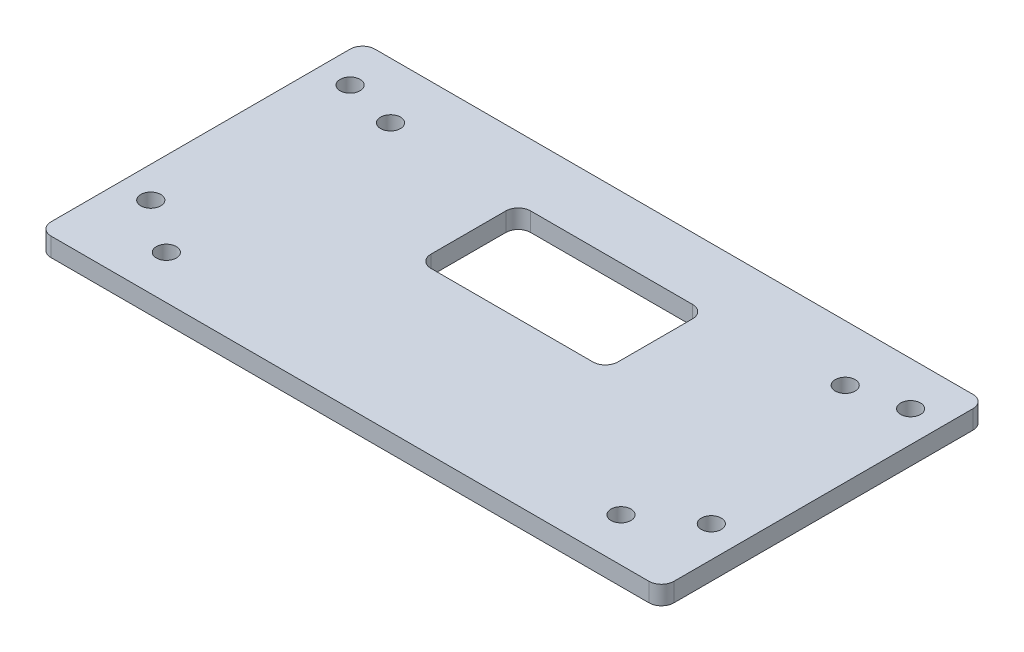
SolidWorks part; units mm, degrees
ref_plane "前视基准面" through (0, 0, 0) normal (0, 0, 1) x (1, 0, 0)
ref_plane "上视基准面" through (0, 0, 0) normal (0, 1, 0) x (1, 0, 0)
ref_plane "右视基准面" through (0, 0, 0) normal (1, 0, 0) x (0, 0, -1)
sketch "草图1" plane through (0, 0, 0) normal (0, 1, 0) x (1, 0, 0)
  line L0 (0, 26) -> (0, -26) construction
  line L1 (-50, -26) -> (50, -26)
  line L2 (-50, -26) -> (-50, 26)
  line L3 (-50, 26) -> (50, 26)
  line L4 (50, -26) -> (50, 26)
  line L5 (-50, -26) -> (50, 26) construction
  line L6 (-50, 26) -> (50, -26) construction
  line L7 (-50, 0) -> (50, 0) construction
  line L9 (-13, 0) -> (13, 0)
  line L10 (-15, 2) -> (-15, 14)
  line L11 (-13, 16) -> (13, 16)
  line L12 (15, 2) -> (15, 14)
  line L13 (-15, 0) -> (15, 16) construction
  line L14 (-15, 16) -> (15, 0) construction
  circle A0 centre (-36.5, 17) radius 1.6
  circle A1 centre (36.5, 17) radius 1.6
  circle A2 centre (36.5, -19) radius 1.6
  circle A3 centre (-36.5, -19) radius 1.6
  circle A4 centre (-45, 19) radius 1.6
  circle A7 centre (45, 19) radius 1.6
  arc A8 (13, 0) -> (15, 2) centre (13, 2) ccw
  arc A9 (13, 16) -> (15, 14) centre (13, 14) cw
  arc A10 (-13, 0) -> (-15, 2) centre (-13, 2) cw
  arc A11 (-15, 14) -> (-13, 16) centre (-13, 14) cw
  circle A12 centre (-45, -13) radius 1.6
  circle A13 centre (45, -13) radius 1.6
  point P0 (0, 0)
  point P26 (0, 8)
  dimension "D3" = 3.2
  dimension "D4" = 36.5
  dimension "D5" = 17
  dimension "D8" = 3.2
  dimension "D9" = 19
  dimension "D10" = 45
  dimension "D14" = 2
  dimension "D1" = 100
  dimension "D2" = 52
  dimension "D11" = 30
  dimension "D12" = 16
  dimension "D13" = 0
  dimension "D6" = 2
  dimension "D7" = 2
  dimension "D15" = 2
extrude "凸台-拉伸1" add sketch "草图1" along normal blind 3
fillet "圆角1" radius 2 4 edges at (50, 1.5, -26) (50, 1.5, 26) (-50, 1.5, 26) (-50, 1.5, -26)
